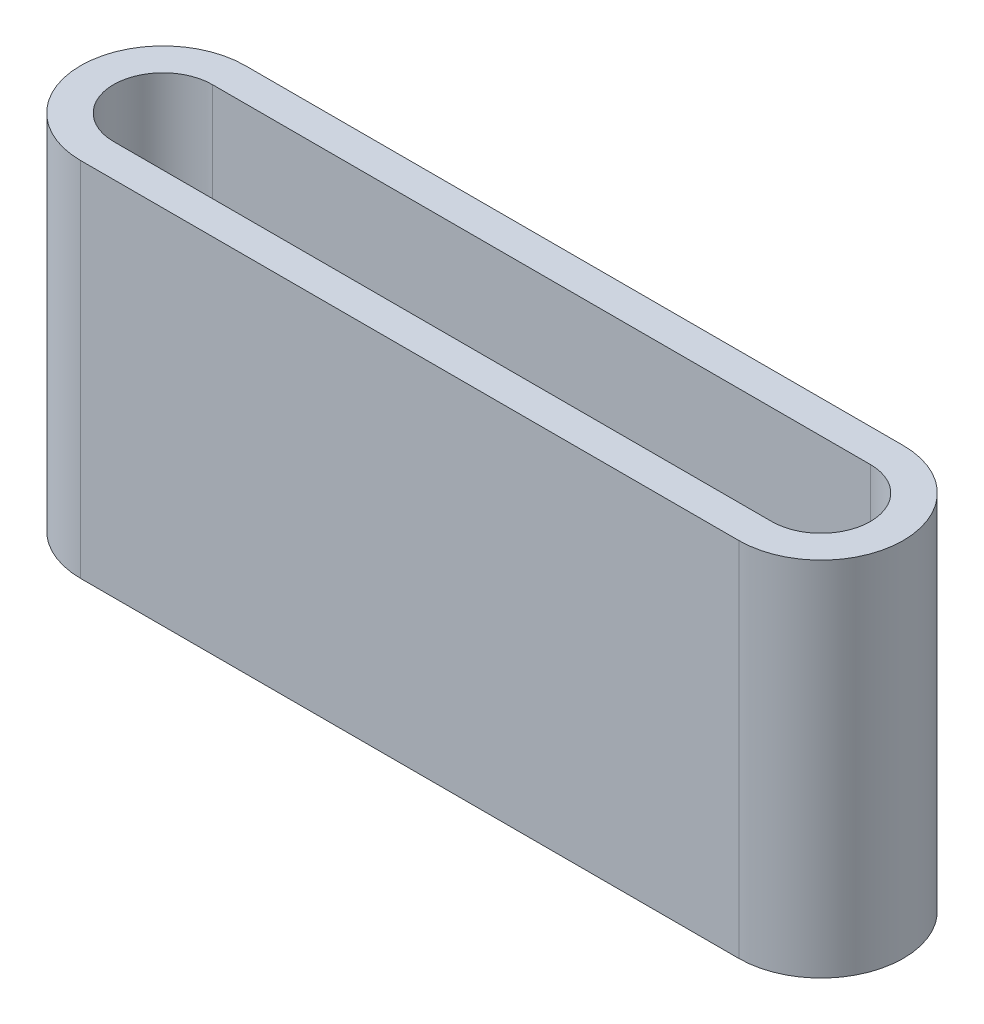
SolidWorks part; units mm, degrees
ref_plane "前视基准面" through (0, 0, 0) normal (0, 0, 1) x (1, 0, 0)
ref_plane "上视基准面" through (0, 0, 0) normal (0, 1, 0) x (1, 0, 0)
ref_plane "右视基准面" through (0, 0, 0) normal (1, 0, 0) x (0, 0, -1)
other "Configuration Table"
sketch "草图1" plane through (0, 0, 0) normal (0, 1, 0) x (1, 0, 0)
  line L0 (0, 0) -> (100, 0) construction
  line L1 (0, 12.5) -> (100, 12.5)
  line L2 (0, -12.5) -> (100, -12.5)
  arc A0 (0, 12.5) -> (0, -12.5) centre (0, 0) ccw
  arc A1 (100, -12.5) -> (100, 12.5) centre (100, 0) ccw
  point P3 (50, 0)
  dimension "D1" = 100
  dimension "D2" = 25
extrude "凸台-拉伸1" add sketch "草图1" along normal blind 20
sketch "草图2" plane through (0, 0, 0) normal (0, -1, 0) x (1, 0, 0)
  line L2 (100, 12.5) -> (0, 12.5)
  line L3 (0, -12.5) -> (100, -12.5)
  line L4 (100, 12.5) -> (0, 12.5)
  line L5 (0, -12.5) -> (100, -12.5)
  arc A2 (0, 12.5) -> (0, -12.5) centre (0, 0) ccw
  arc A3 (100, -12.5) -> (100, 12.5) centre (100, 0) ccw
  arc A4 (0, 12.5) -> (0, -12.5) centre (0, 0) ccw
  arc A5 (100, -12.5) -> (100, 12.5) centre (100, 0) ccw
  dimension "D1" = 0
extrude "拉伸-薄壁1" add sketch "草图2" against normal blind 55 thin thin type one direction reverse wall 5
